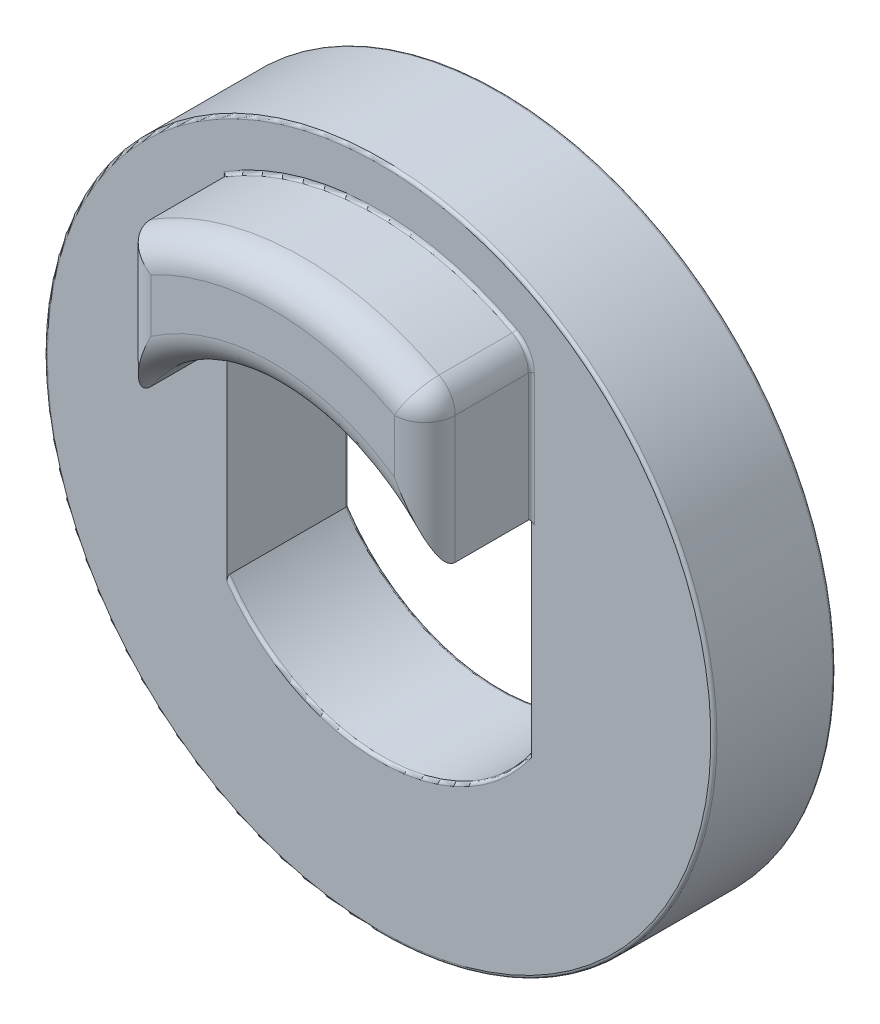
SolidWorks part; units mm, degrees
ref_plane "Alzado" through (0, 0, 0) normal (0, 0, 1) x (1, 0, 0)
ref_plane "Planta" through (0, 0, 0) normal (0, 1, 0) x (1, 0, 0)
ref_plane "Vista lateral" through (0, 0, 0) normal (1, 0, 0) x (0, 0, -1)
sketch "Croquis2" plane through (0, 0, 0) normal (1, 0, 0) x (0, 0, -1)
  line L0 (-7.5, 6) -> (0, 6)
  line L1 (-7.5, 0) -> (7.5, 0) construction
  line L2 (-7.5, 6) -> (-7.5, 9.5)
  line L3 (-7.5, 9.5) -> (-4, 9.5)
  line L4 (-4, 9.5) -> (-4, 11)
  line L5 (-4, 11) -> (0, 11)
  line L6 (0, 11) -> (0, 6)
  point P3 (-3.75, 6)
  point P7 (0, 0)
  dimension "D1" = 12
  dimension "D2" = 7.5
  dimension "D3" = 3.5
  dimension "D4" = 3.5
  dimension "D5" = 1.5
revolve "Revolución1" add sketch "Croquis2" angle 360 about L1
sketch "Croquis3" plane through (0, 0, 7.5) normal (0, 0, 1) x (1, 0, 0)
  line L1 (-5, 8.0777) -> (5, 8.0777)
  line L2 (-5, 8.0777) -> (-5, -8.0777)
  line L3 (-5, -8.0777) -> (5, -8.0777)
  line L4 (5, 8.0777) -> (5, -8.0777)
  line L5 (-5, 8.0777) -> (5, -8.0777) construction
  line L6 (-5, -8.0777) -> (5, 8.0777) construction
  circle A0 centre (0, 0) radius 9.5 construction
  circle A1 centre (0, 0) radius 6 construction
  circle A2 centre (0, 0) radius 9.5
  circle A3 centre (0, 0) radius 6
  circle M5 centre (0, 0) radius 6
  dimension "D1" = 10
extrude "Saliente-Extruir1" add sketch "Croquis3" against normal through all contours L4 M5 | L2 M5
sketch "Croquis4" plane through (0, 0, 7.5) normal (0, 0, 1) x (1, 0, 0)
  line L0 (5, 3.3166) -> (5, -3.3166) construction
  line L1 (-5, 8.0777) -> (5, 8.0777)
  line L2 (-5, 8.0777) -> (-5, -8.0777)
  line L3 (-5, -8.0777) -> (5, -8.0777)
  line L4 (5, 8.0777) -> (5, -8.0777)
  line L5 (-5, 8.0777) -> (5, -8.0777) construction
  line L6 (-5, -8.0777) -> (5, 8.0777) construction
  circle A0 centre (0, 0) radius 9.5 construction
  circle A1 centre (0, 0) radius 9.5
  point P9 (5, 0)
  point P10 (5, 0)
  line M3 (5, 3.3166) -> (5, -3.3166)
  arc M4 (5, -3.3166) -> (-5, -3.3166) centre (0, 0) cw
  line M5 (-5, -3.3166) -> (-5, 3.3166)
  circle M6 centre (0, 0) radius 9.5
extrude "Cortar-Extruir1" cut sketch "Croquis4" against normal up to surface (3.5 mm away) contours L4 M6 M3 | L2 M6 M5 | L4 L2 L3 M4 | L3 M6 up to face at (9.5, 0, 4)
fillet "Redondeo1" radius 1 5 edges at (-5, 5.6972, 7.5) (0, 6, 7.5) (5, 5.6972, 7.5) (5, 8.0777, 5.75) (0, 9.5, 7.5)
fillet "Redondeo2" radius 0.1 11 edges at (-0.3054, 9.4951, 4) (4.8575, 8.0145, 4) (0, -6, 4) (-5, 5.6972, 4) (5, 5.4083, 4) (11, 0, 0) (11, 0, 4) (-5, 0, 0) (5, 0, 0) (0, 6, 0) (0, -6, 0)
